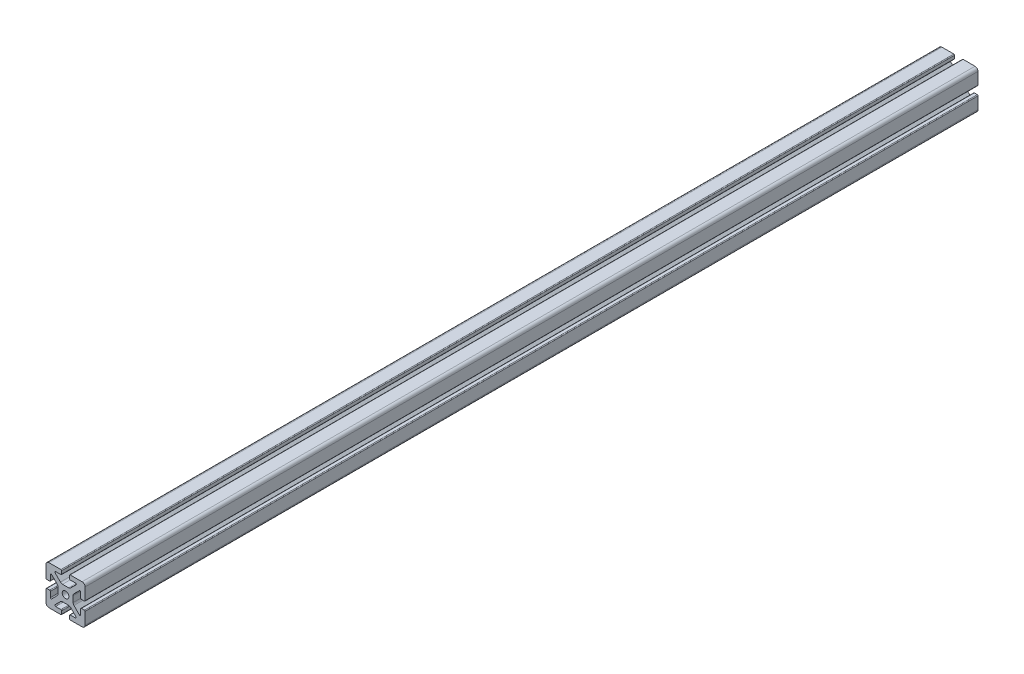
SolidWorks part; units mm, degrees
ref_plane "Front Plane" through (0, 0, 0) normal (0, 0, 1) x (1, 0, 0)
ref_plane "Top Plane" through (0, 0, 0) normal (0, 1, 0) x (1, 0, 0)
ref_plane "Right Plane" through (0, 0, 0) normal (1, 0, 0) x (0, 0, -1)
sketch "Sketch1" plane through (0, 0, 0) normal (0, 0, 1) x (1, 0, 0)
  line L2 (-20, 16.952) -> (-20, 4.7625)
  line L3 (-16.952, 20) -> (-4.7625, 20)
  line L4 (-4.0005, 19.238) -> (-4.0005, 16.2662)
  line L5 (-4.7625, 15.5042) -> (-10.2235, 15.5042)
  line L6 (-10.7623, 14.2034) -> (-5.194, 8.6351)
  line L7 (-14.2034, 10.7623) -> (-8.6351, 5.194)
  line L8 (-15.5042, 10.2235) -> (-15.5042, 4.7625)
  line L9 (-16.2662, 4.0005) -> (-19.238, 4.0005)
  line L11 (-3.0746, 7.7572) -> (3.0746, 7.7572)
  line L12 (-7.7572, 3.0746) -> (-7.7572, -3.0746)
  line L13 (16.2662, 4.0005) -> (19.238, 4.0005)
  line L14 (15.5042, 10.2235) -> (15.5042, 4.7625)
  line L15 (20, 16.952) -> (20, 4.7625)
  line L16 (16.952, 20) -> (4.7625, 20)
  line L17 (4.0005, 19.238) -> (4.0005, 16.2662)
  line L18 (4.7625, 15.5042) -> (10.2235, 15.5042)
  line L19 (7.7572, 3.0746) -> (7.7572, -3.0746)
  line L20 (10.7623, 14.2034) -> (5.194, 8.6351)
  line L21 (14.2034, 10.7623) -> (8.6351, 5.194)
  line L22 (-16.2662, -4.0005) -> (-19.238, -4.0005)
  line L23 (-15.5042, -10.2235) -> (-15.5042, -4.7625)
  line L24 (-14.2034, -10.7623) -> (-8.6351, -5.194)
  line L25 (-10.7623, -14.2034) -> (-5.194, -8.6351)
  line L26 (-4.7625, -15.5042) -> (-10.2235, -15.5042)
  line L27 (-4.0005, -19.238) -> (-4.0005, -16.2662)
  line L28 (-16.952, -20) -> (-4.7625, -20)
  line L29 (-20, -16.952) -> (-20, -4.7625)
  line L30 (20, -16.952) -> (20, -4.7625)
  line L31 (16.952, -20) -> (4.7625, -20)
  line L32 (4.0005, -19.238) -> (4.0005, -16.2662)
  line L33 (4.7625, -15.5042) -> (10.2235, -15.5042)
  line L34 (10.7623, -14.2034) -> (5.194, -8.6351)
  line L35 (14.2034, -10.7623) -> (8.6351, -5.194)
  line L36 (15.5042, -10.2235) -> (15.5042, -4.7625)
  line L37 (16.2662, -4.0005) -> (19.238, -4.0005)
  line L38 (-3.0746, -7.7572) -> (3.0746, -7.7572)
  circle A0 centre (0, 0) radius 3.4036
  arc A1 (-20, 16.952) -> (-16.952, 20) centre (-16.952, 16.952) cw
  arc A2 (-14.2034, 10.7623) -> (-15.5042, 10.2235) centre (-14.7422, 10.2235) ccw
  arc A3 (-10.2235, 15.5042) -> (-10.7623, 14.2034) centre (-10.2235, 14.7422) ccw
  arc A4 (-4.7625, 20) -> (-4.0005, 19.238) centre (-4.7625, 19.238) cw
  arc A5 (-20, 4.7625) -> (-19.238, 4.0005) centre (-19.238, 4.7625) ccw
  arc A6 (-15.5042, 4.7625) -> (-16.2662, 4.0005) centre (-16.2662, 4.7625) cw
  arc A7 (-4.0005, 16.2662) -> (-4.7625, 15.5042) centre (-4.7625, 16.2662) cw
  arc A8 (-3.0746, 7.7572) -> (-5.194, 8.6351) centre (-3.0746, 10.7544) cw
  arc A9 (-7.7572, 3.0746) -> (-8.6351, 5.194) centre (-10.7544, 3.0746) ccw
  arc A10 (15.5042, 4.7625) -> (16.2662, 4.0005) centre (16.2662, 4.7625) ccw
  arc A11 (20, 4.7625) -> (19.238, 4.0005) centre (19.238, 4.7625) cw
  arc A12 (20, 16.952) -> (16.952, 20) centre (16.952, 16.952) ccw
  arc A13 (4.7625, 20) -> (4.0005, 19.238) centre (4.7625, 19.238) ccw
  arc A14 (4.0005, 16.2662) -> (4.7625, 15.5042) centre (4.7625, 16.2662) ccw
  arc A15 (3.0746, 7.7572) -> (5.194, 8.6351) centre (3.0746, 10.7544) ccw
  arc A16 (7.7572, 3.0746) -> (8.6351, 5.194) centre (10.7544, 3.0746) cw
  arc A17 (14.2034, 10.7623) -> (15.5042, 10.2235) centre (14.7422, 10.2235) cw
  arc A18 (10.2235, 15.5042) -> (10.7623, 14.2034) centre (10.2235, 14.7422) cw
  arc A19 (-7.7572, -3.0746) -> (-8.6351, -5.194) centre (-10.7544, -3.0746) cw
  arc A20 (-3.0746, -7.7572) -> (-5.194, -8.6351) centre (-3.0746, -10.7544) ccw
  arc A21 (-4.0005, -16.2662) -> (-4.7625, -15.5042) centre (-4.7625, -16.2662) ccw
  arc A22 (-15.5042, -4.7625) -> (-16.2662, -4.0005) centre (-16.2662, -4.7625) ccw
  arc A23 (-20, -4.7625) -> (-19.238, -4.0005) centre (-19.238, -4.7625) cw
  arc A24 (-4.7625, -20) -> (-4.0005, -19.238) centre (-4.7625, -19.238) ccw
  arc A25 (-10.2235, -15.5042) -> (-10.7623, -14.2034) centre (-10.2235, -14.7422) cw
  arc A26 (-14.2034, -10.7623) -> (-15.5042, -10.2235) centre (-14.7422, -10.2235) cw
  arc A27 (-20, -16.952) -> (-16.952, -20) centre (-16.952, -16.952) ccw
  arc A28 (20, -16.952) -> (16.952, -20) centre (16.952, -16.952) cw
  arc A29 (14.2034, -10.7623) -> (15.5042, -10.2235) centre (14.7422, -10.2235) ccw
  arc A30 (10.2235, -15.5042) -> (10.7623, -14.2034) centre (10.2235, -14.7422) ccw
  arc A31 (4.7625, -20) -> (4.0005, -19.238) centre (4.7625, -19.238) cw
  arc A32 (20, -4.7625) -> (19.238, -4.0005) centre (19.238, -4.7625) ccw
  arc A33 (15.5042, -4.7625) -> (16.2662, -4.0005) centre (16.2662, -4.7625) cw
  arc A34 (4.0005, -16.2662) -> (4.7625, -15.5042) centre (4.7625, -16.2662) cw
  arc A35 (3.0746, -7.7572) -> (5.194, -8.6351) centre (3.0746, -10.7544) cw
  arc A36 (7.7572, -3.0746) -> (8.6351, -5.194) centre (10.7544, -3.0746) ccw
extrude "Boss-Extrude1" add sketch "Sketch1" along normal mid plane 914.4
